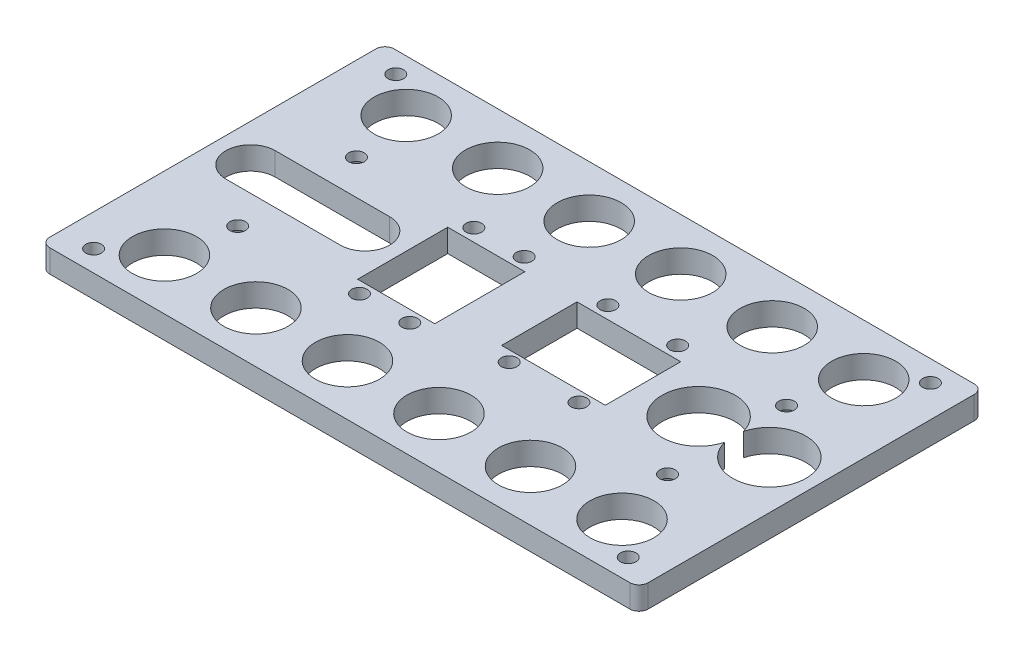
SolidWorks part; units mm, degrees
ref_plane "Front Plane" through (0, 0, 0) normal (0, 0, 1) x (1, 0, 0)
ref_plane "Top Plane" through (0, 0, 0) normal (0, 1, 0) x (1, 0, 0)
ref_plane "Right Plane" through (0, 0, 0) normal (1, 0, 0) x (0, 0, -1)
sketch "Sketch1" plane through (0, 0, 0) normal (0, 1, 0) x (1, 0, 0)
  line L0 (-57.1314, 0) -> (-32.1314, 0) construction
  line L5 (-23.7897, 9.7468) -> (-6.9381, 9.7468)
  line L6 (-23.7897, 9.7468) -> (-23.7897, -9.9429)
  line L7 (-23.7897, -9.9429) -> (-6.9381, -9.9429)
  line L8 (-6.9381, 9.7468) -> (-6.9381, -9.9429)
  line L9 (4.4674, 9.7468) -> (27.1321, 9.7468)
  line L10 (4.4674, 9.7468) -> (4.4674, -6.7386)
  line L11 (4.4674, -6.7386) -> (27.1321, -6.7386)
  line L12 (27.1321, 9.7468) -> (27.1321, -6.7386)
  line L13 (-65.3914, 37.6297) -> (65.3914, 37.6297)
  line L14 (-65.3914, 37.6297) -> (-65.3914, -37.6297)
  line L15 (-65.3914, -37.6297) -> (65.3914, -37.6297)
  line L16 (65.3914, 37.6297) -> (65.3914, -37.6297)
  line L17 (-65.3914, 37.6297) -> (65.3914, -37.6297) construction
  line L18 (-65.3914, -37.6297) -> (65.3914, 37.6297) construction
  line L19 (-57.1314, 5.3866) -> (-32.1314, 5.3866)
  line L20 (-57.1314, -5.3866) -> (-32.1314, -5.3866)
  circle A0 centre (-58.42, 33.02) radius 1.7
  circle A1 centre (-58.42, -33.02) radius 1.7
  circle A2 centre (58.42, 33.02) radius 1.7
  circle A3 centre (58.42, -33.02) radius 1.7
  circle A4 centre (-20.8388, 12.5) radius 1.7
  circle A5 centre (-20.8388, -12.5) radius 1.7
  circle A6 centre (-9.8388, 12.5) radius 1.7
  circle A7 centre (-9.8388, -12.5) radius 1.7
  circle A8 centre (8.4683, 12.485) radius 1.7
  circle A9 centre (8.4683, -9.09) radius 1.7
  circle A10 centre (23.7083, 12.5) radius 1.7
  circle A11 centre (23.7083, -9.09) radius 1.7
  circle A12 centre (-47, 13) radius 1.7
  circle A13 centre (-46.9521, -13) radius 1.7
  circle A14 centre (47, 13) radius 1.7
  circle A15 centre (47, -13) radius 1.7
  circle A16 centre (-49.4809, 26.3512) radius 7
  circle A17 centre (-29.4809, 26.3512) radius 7
  circle A18 centre (-9.4809, 26.3512) radius 7
  circle A19 centre (10.5191, 26.3512) radius 7
  circle A20 centre (30.5191, 26.3512) radius 7
  circle A21 centre (50.5191, 26.3512) radius 7
  circle A22 centre (-49.4809, -26.48) radius 7
  circle A23 centre (-29.4809, -26.48) radius 7
  circle A24 centre (-9.4809, -26.48) radius 7
  circle A25 centre (10.5191, -26.48) radius 7
  circle A26 centre (30.5191, -26.48) radius 7
  circle A27 centre (50.5191, -26.48) radius 7
  arc A28 (-57.1314, 5.3866) -> (-57.1314, -5.3866) centre (-57.1314, 0) ccw
  arc A29 (-32.1314, -5.3866) -> (-32.1314, 5.3866) centre (-32.1314, 0) ccw
  arc A32 (47.1615, 3.4086) -> (47.1615, -0.7026) centre (39.4301, 1.353) ccw
  arc A34 (47.1615, -0.7026) -> (47.1615, 3.4086) centre (54.8929, 1.353) ccw
  point P0 (0, 0)
  point P72 (-44.6314, 0)
  point P79 (39.4301, 1.353)
  point P82 (56.3103, 1.353)
  point P83 (0, 0)
  point P84 (0, 0)
  point P85 (0, 0)
  point P86 (0, 0)
  point P87 (54.8929, 1.353)
  dimension "D3" = 33.02
  dimension "D4" = 116.84
  dimension "D5" = 33.02
  dimension "D7" = 11
  dimension "D10" = 13
  dimension "D13" = 58.42
  dimension "D18" = 94
  dimension "D9" = 47
  dimension "D14" = 6
  dimension "D15" = 6
  dimension "D6" = 26
  dimension "D8" = 25
  dimension "D11" = 21.59
  dimension "D12" = 15.24
  dimension "D21" = 0
  dimension "D22" = 25
  dimension "D23" = 11
extrude "Boss-Extrude3" add sketch "Sketch1" along normal blind 5
sketch "Sketch2" plane through (0, 0, 0) normal (0, -1, 0) x (1, 0, 0)
  line L13 (-50.1177, -13) -> (-48.5588, -15.7)
  line L14 (-48.5588, -15.7) -> (-45.4412, -15.7)
  line L15 (-45.4412, -15.7) -> (-43.8823, -13)
  line L16 (-43.8823, -13) -> (-45.4412, -10.3)
  line L17 (-45.4412, -10.3) -> (-48.5588, -10.3)
  line L18 (-48.5588, -10.3) -> (-50.1177, -13)
  line L19 (-50.0698, 13) -> (-48.511, 10.3)
  line L20 (-48.511, 10.3) -> (-45.3933, 10.3)
  line L21 (-45.3933, 10.3) -> (-43.8344, 13)
  line L22 (-43.8344, 13) -> (-45.3933, 15.7)
  line L23 (-45.3933, 15.7) -> (-48.511, 15.7)
  line L24 (-48.511, 15.7) -> (-50.0698, 13)
  line L25 (43.8823, -13) -> (45.4412, -15.7)
  line L26 (45.4412, -15.7) -> (48.5588, -15.7)
  line L27 (48.5588, -15.7) -> (50.1177, -13)
  line L28 (50.1177, -13) -> (48.5588, -10.3)
  line L29 (48.5588, -10.3) -> (45.4412, -10.3)
  line L30 (45.4412, -10.3) -> (43.8823, -13)
  line L31 (43.8823, 13) -> (45.4412, 10.3)
  line L32 (45.4412, 10.3) -> (48.5588, 10.3)
  line L33 (48.5588, 10.3) -> (50.1177, 13)
  line L34 (50.1177, 13) -> (48.5588, 15.7)
  line L35 (48.5588, 15.7) -> (45.4412, 15.7)
  line L36 (45.4412, 15.7) -> (43.8823, 13)
  circle A0 centre (47, -13) radius 2.7 construction
  circle A1 centre (47, 13) radius 2.7 construction
  circle A2 centre (-47, -13) radius 2.7 construction
  circle A3 centre (-46.9521, 13) radius 2.7 construction
extrude "Cut-Extrude1" cut sketch "Sketch2" against normal blind 3
fillet "Fillet1" radius 2 4 edges at (-65.3914, 2.5, 37.6297) (65.3914, 2.5, 37.6297) (65.3914, 2.5, -37.6297) (-65.3914, 2.5, -37.6297)
